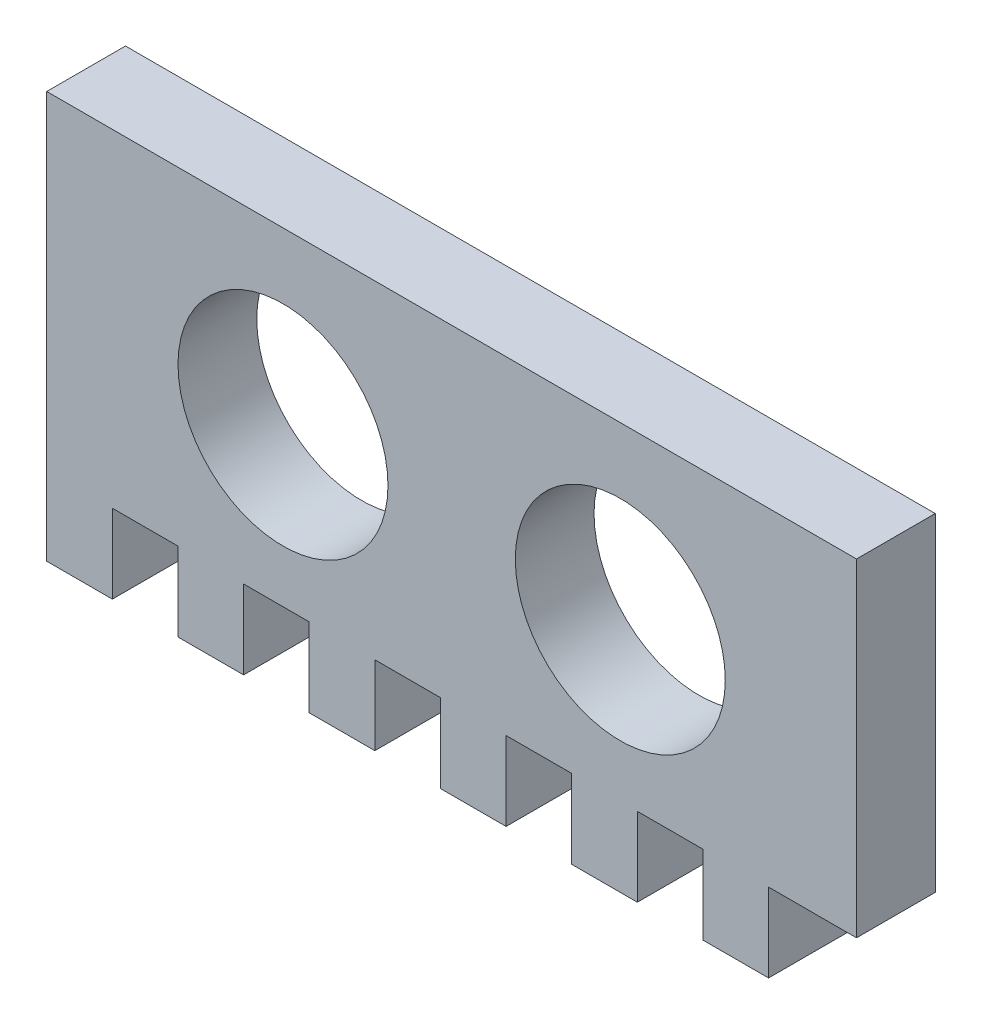
SolidWorks part; units mm, degrees
ref_plane "Plan de face" through (0, 0, 0) normal (0, 0, 1) x (1, 0, 0)
ref_plane "Plan de dessus" through (0, 0, 0) normal (0, 1, 0) x (1, 0, 0)
ref_plane "Plan de droite" through (0, 0, 0) normal (1, 0, 0) x (0, 0, -1)
sketch "Esquisse1" plane through (0, 0, 0) normal (0, 0, 1) x (1, 0, 0)
  line L0 (0, 0) -> (0, 31)
  line L1 (0, 31) -> (61.7, 31)
  line L2 (61.7, 31) -> (61.7, 6)
  line L3 (0, 0) -> (5, 0)
  line L4 (5, 0) -> (5, 6)
  line L5 (5, 6) -> (10, 6)
  line L6 (10, 6) -> (10, 0)
  line L7 (10, 0) -> (15, 0)
  line L8 (15, 0) -> (15, 6)
  line L9 (15, 6) -> (20, 6)
  line L10 (20, 6) -> (20, 0)
  line L11 (20, 0) -> (25, 0)
  line L12 (25, 0) -> (25, 6)
  line L13 (25, 6) -> (30, 6)
  line L14 (30, 6) -> (30, 0)
  line L15 (30, 0) -> (35, 0)
  line L16 (35, 0) -> (35, 6)
  line L17 (35, 6) -> (40, 6)
  line L18 (40, 6) -> (40, 0)
  line L19 (40, 0) -> (45, 0)
  line L20 (45, 0) -> (45, 6)
  line L21 (45, 6) -> (50, 6)
  line L22 (50, 6) -> (50, 0)
  line L23 (50, 0) -> (55, 0)
  line L24 (55, 0) -> (55, 6)
  line L25 (55, 6) -> (61.7, 6)
  circle A0 centre (18, 18) radius 8
  circle A1 centre (43.7, 18) radius 8
  point P3 (0, 0)
  dimension "D1" = 16
  dimension "D2" = 16
  dimension "D3" = 25.7
  dimension "D4" = 18
  dimension "D9" = 12
  dimension "D10" = 13
  dimension "D5" = 18
  dimension "D6" = 5
  dimension "D7" = 5
  dimension "D11" = 6
extrude "Boss.-Extru.1" add sketch "Esquisse1" along normal blind 6
